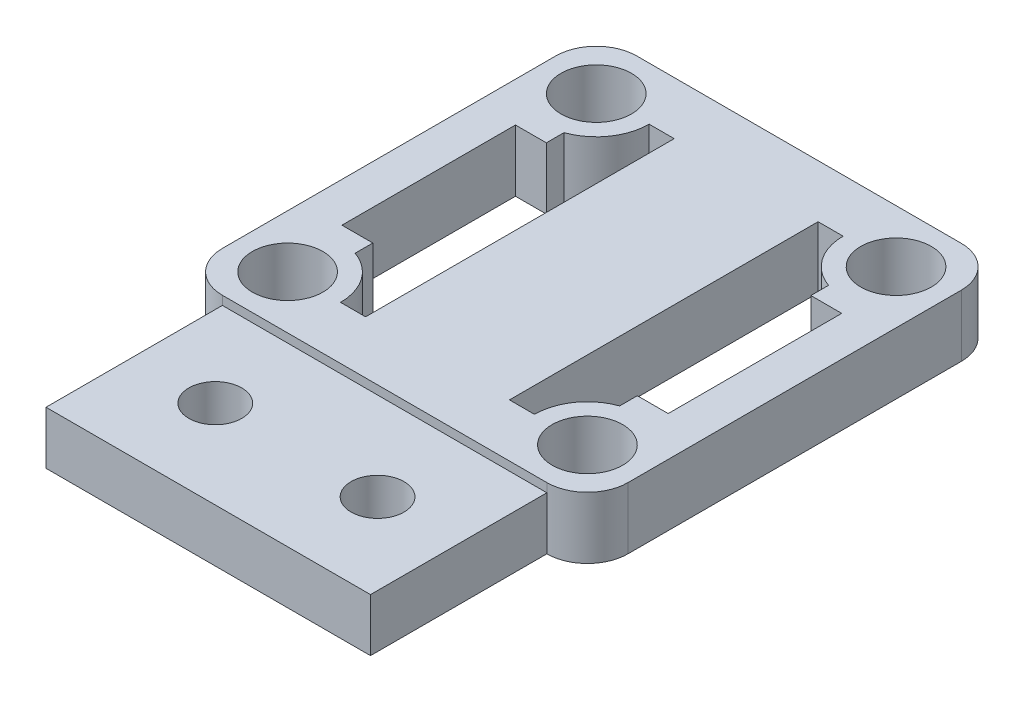
SolidWorks part; units mm, degrees
ref_plane "Front Plane" through (0, 0, 0) normal (0, 0, 1) x (1, 0, 0)
ref_plane "Top Plane" through (0, 0, 0) normal (0, 1, 0) x (1, 0, 0)
ref_plane "Right Plane" through (0, 0, 0) normal (1, 0, 0) x (0, 0, -1)
sketch "Sketch1" plane through (0, 0, 0) normal (0, 1, 0) x (1, 0, 0)
  line L1 (-12.6491, 14.6331) -> (5.7509, 14.6331)
  line L2 (-14.9491, 12.3331) -> (-14.9491, -6.5669)
  line L3 (-12.6491, -8.8669) -> (5.7509, -8.8669)
  line L4 (8.0509, 12.3331) -> (8.0509, -6.5669)
  line L5 (-14.9491, 14.6331) -> (8.0509, -8.8669) construction
  line L6 (-14.9491, -8.8669) -> (8.0509, 14.6331) construction
  arc A0 (8.0509, 12.3331) -> (5.7509, 14.6331) centre (5.7509, 12.3331) ccw
  arc A1 (-12.6491, -8.8669) -> (-14.9491, -6.5669) centre (-12.6491, -6.5669) cw
  arc A2 (5.7509, -8.8669) -> (8.0509, -6.5669) centre (5.7509, -6.5669) ccw
  arc A3 (-14.9491, 12.3331) -> (-12.6491, 14.6331) centre (-12.6491, 12.3331) cw
  point P0 (-3.4491, 2.8831)
  dimension "D3" = 2.3
  dimension "D4" = 2.3
  dimension "D1" = 23.5
  dimension "D2" = 23
extrude "Boss-Extrude1" add sketch "Sketch1" along normal blind 2
sketch "Sketch2" plane through (0, 2, 0) normal (0, 1, 0) x (1, 0, 0)
  line L8 (5.7509, 13.6331) -> (-12.6491, 13.6331)
  line L9 (-13.9491, 12.3331) -> (-13.9491, -6.5669)
  line L10 (-12.6491, -7.8669) -> (5.7509, -7.8669)
  line L11 (7.0509, -6.5669) -> (7.0509, 12.3331)
  line L12 (5.7509, 13.6331) -> (-12.6491, 13.6331)
  line L13 (-13.9491, 12.3331) -> (-13.9491, -6.5669)
  line L14 (-12.6491, -7.8669) -> (5.7509, -7.8669)
  line L15 (7.0509, -6.5669) -> (7.0509, 12.3331)
  arc A8 (7.0509, 12.3331) -> (5.7509, 13.6331) centre (5.7509, 12.3331) ccw
  arc A9 (-12.6491, 13.6331) -> (-13.9491, 12.3331) centre (-12.6491, 12.3331) ccw
  arc A10 (-13.9491, -6.5669) -> (-12.6491, -7.8669) centre (-12.6491, -6.5669) ccw
  arc A11 (5.7509, -7.8669) -> (7.0509, -6.5669) centre (5.7509, -6.5669) ccw
  arc A12 (7.0509, 12.3331) -> (5.7509, 13.6331) centre (5.7509, 12.3331) ccw
  arc A13 (-12.6491, 13.6331) -> (-13.9491, 12.3331) centre (-12.6491, 12.3331) ccw
  arc A14 (-13.9491, -6.5669) -> (-12.6491, -7.8669) centre (-12.6491, -6.5669) ccw
  arc A15 (5.7509, -7.8669) -> (7.0509, -6.5669) centre (5.7509, -6.5669) ccw
  dimension "D1" = 1
extrude "Cut-Extrude2" cut sketch "Sketch2" against normal blind 1
sketch "Sketch5" plane through (0, 1, 0) normal (0, 1, 0) x (1, 0, 0)
  line L0 (-3.4491, 13.6331) -> (-3.4491, -7.8669) construction
  line L1 (5.7509, 13.6331) -> (-12.6491, 13.6331) construction
  line L2 (-12.6491, -7.8669) -> (5.7509, -7.8669) construction
  line L3 (7.0509, 2.8831) -> (-13.9491, 2.8831) construction
  line L4 (7.0509, -6.5669) -> (7.0509, 12.3331) construction
  line L5 (-13.9491, 12.3331) -> (-13.9491, -6.5669) construction
  circle A0 centre (5.0509, 11.6331) radius 2
  circle A1 centre (5.0509, -5.8669) radius 2
  circle A2 centre (-11.9491, -5.8669) radius 2
  circle A3 centre (-11.9491, 11.6331) radius 2
  dimension "D1" = 4
extrude "Cut-Extrude3" cut sketch "Sketch5" against normal through all
sketch "Sketch6" plane through (0, 1, 0) normal (0, 1, 0) x (1, 0, 0)
  line L0 (-14.9491, 12.3331) -> (-14.9491, -6.5669) construction
  line L1 (8.0509, -6.5669) -> (8.0509, 12.3331) construction
  line L14 (4.0509, -5.8669) -> (4.0509, 11.6331)
  line L15 (4.0509, -3.0385) -> (4.0509, 8.8047)
  line L16 (2.0509, 11.6331) -> (2.0509, -5.8669)
  line L17 (-10.9491, 12.3331) -> (-10.9491, -6.5669)
  line L18 (-10.9491, 8.8047) -> (-10.9491, -3.0385)
  line L19 (-8.9491, 11.6331) -> (-8.9491, -5.8669)
  arc A5 (-11.9491, -8.8669) -> (-14.9491, -5.8669) centre (-11.9491, -5.8669) ccw
  arc A6 (-8.9491, -5.8669) -> (-10.9491, -3.0385) centre (-11.9491, -5.8669) ccw
  arc A20 (5.0509, 14.6331) -> (8.0509, 11.6331) centre (5.0509, 11.6331) ccw
  arc A21 (2.0509, 11.6331) -> (4.0509, 8.8047) centre (5.0509, 11.6331) ccw
  arc A23 (-14.9491, 11.6331) -> (-11.9491, 14.6331) centre (-11.9491, 11.6331) ccw
  arc A24 (-10.9491, 8.8047) -> (-8.9491, 11.6331) centre (-11.9491, 11.6331) ccw
  arc A26 (8.0509, -5.8669) -> (5.0509, -8.8669) centre (5.0509, -5.8669) ccw
  arc A27 (4.0509, -3.0385) -> (2.0509, -5.8669) centre (5.0509, -5.8669) ccw
  dimension "D1" = 23
  dimension "D2" = 1
  dimension "D3" = 1
  dimension "D4" = 1
  dimension "D5" = 1
  dimension "D6" = 3
  dimension "D7" = 3
extrude "Cut-Extrude4" cut sketch "Sketch6" against normal through all
sketch "Sketch7" plane through (0, 0, 8.8669) normal (0, 0, 1) x (1, 0, 0)
  line L0 (-14.9491, 2) -> (-14.9491, 0) construction
  line L1 (8.0509, 2) -> (8.0509, 0) construction
  line L2 (-12.6491, 2) -> (-12.6491, 0) construction
  line L3 (-12.6491, 1) -> (5.7509, 1)
  line L4 (5.7509, 2) -> (5.7509, 0) construction
  line L5 (5.7509, 1) -> (5.7509, 0)
  line L6 (5.7509, 0) -> (-12.6491, 0)
  line L7 (-12.6491, 0) -> (-12.6491, 1)
  line L8 (-12.6491, 2) -> (5.7509, 2) construction
  dimension "D1" = 23
extrude "Boss-Extrude2" add sketch "Sketch7" along normal blind 10
sketch "Sketch8" plane through (0, 1, 0) normal (0, 1, 0) x (1, 0, 0)
  line L0 (-12.6491, -8.8669) -> (5.7509, -8.8669) construction
  line L1 (-12.6491, -18.8669) -> (-12.6491, -8.8669) construction
  line L2 (5.7509, -18.8669) -> (5.7509, -8.8669) construction
  line L3 (-3.4491, -8.8669) -> (-3.4491, -18.8669) construction
  line L4 (5.7509, -18.8669) -> (-12.6491, -18.8669) construction
  circle A0 centre (1.1509, -13.8669) radius 1.5
  circle A1 centre (-8.0491, -13.8669) radius 1.5
  dimension "D2" = 3
  dimension "D1" = 5
  dimension "D3" = 18.4
  dimension "D4" = 4.6
  dimension "D5" = 4.6
extrude "Cut-Extrude5" cut sketch "Sketch8" against normal through all
sketch "Sketch9" plane through (0, 2, 0) normal (0, 1, 0) x (1, 0, 0)
  line L8 (5.7509, 13.8331) -> (-12.6491, 13.8331)
  line L9 (-14.1491, 12.3331) -> (-14.1491, -6.5669)
  line L10 (-12.6491, -8.0669) -> (5.7509, -8.0669)
  line L11 (7.2509, -6.5669) -> (7.2509, 12.3331)
  line L12 (5.7509, 13.8331) -> (-12.6491, 13.8331)
  line L13 (-14.1491, 12.3331) -> (-14.1491, -6.5669)
  line L14 (-12.6491, -8.0669) -> (5.7509, -8.0669)
  line L15 (7.2509, -6.5669) -> (7.2509, 12.3331)
  arc A8 (7.2509, 12.3331) -> (5.7509, 13.8331) centre (5.7509, 12.3331) ccw
  arc A9 (-12.6491, 13.8331) -> (-14.1491, 12.3331) centre (-12.6491, 12.3331) ccw
  arc A10 (-14.1491, -6.5669) -> (-12.6491, -8.0669) centre (-12.6491, -6.5669) ccw
  arc A11 (5.7509, -8.0669) -> (7.2509, -6.5669) centre (5.7509, -6.5669) ccw
  arc A12 (7.2509, 12.3331) -> (5.7509, 13.8331) centre (5.7509, 12.3331) ccw
  arc A13 (-12.6491, 13.8331) -> (-14.1491, 12.3331) centre (-12.6491, 12.3331) ccw
  arc A14 (-14.1491, -6.5669) -> (-12.6491, -8.0669) centre (-12.6491, -6.5669) ccw
  arc A15 (5.7509, -8.0669) -> (7.2509, -6.5669) centre (5.7509, -6.5669) ccw
  dimension "D1" = 0.8
extrude "Cut-Extrude6" cut sketch "Sketch9" against normal blind 1
sketch "Sketch11" plane through (0, 1, 0) normal (0, 1, 0) x (1, 0, 0)
  line L0 (-8.9491, 11.6331) -> (-7.528, 11.6331)
  line L1 (-7.528, 11.6331) -> (-7.528, -5.8669)
  line L2 (-7.528, -5.8669) -> (-8.9491, -5.8669)
  line L3 (-8.9491, -5.8669) -> (-8.9491, 11.6331)
  line L4 (-3.4491, 13.8331) -> (-3.4491, -8.0669) construction
  line L5 (5.7509, 13.8331) -> (-12.6491, 13.8331) construction
  line L6 (-12.6491, -8.0669) -> (5.7509, -8.0669) construction
  line L7 (0.6299, -5.8669) -> (2.0509, -5.8669)
  line L8 (0.6299, 11.6331) -> (0.6299, -5.8669)
  line L9 (2.0509, 11.6331) -> (0.6299, 11.6331)
  line L10 (2.0509, -5.8669) -> (2.0509, 11.6331)
  line L11 (-10.9491, 8.8047) -> (-10.9491, -3.0385) construction
  line L12 (-12.6991, 7.8031) -> (-10.9491, 7.8031)
  line L13 (-12.6991, 7.8031) -> (-12.6991, -2.0369)
  line L14 (-12.6991, -2.0369) -> (-10.9491, -2.0369)
  line L15 (-10.9491, 7.8031) -> (-10.9491, -2.0369)
  line L16 (5.8009, -2.0369) -> (4.0509, -2.0369)
  line L17 (4.0509, 7.8031) -> (4.0509, -2.0369)
  line L18 (5.8009, 7.8031) -> (4.0509, 7.8031)
  line L19 (5.8009, 7.8031) -> (5.8009, -2.0369)
  point P22 (-10.9491, 2.8831)
  point P23 (-10.9491, 2.8831)
  dimension "D1" = 9.84
  dimension "D2" = 1.75
extrude "Cut-Extrude7" cut sketch "Sketch11" against normal through all
sketch "Sketch12" plane through (0, 0, 0) normal (0, -1, 0) x (1, 0, 0)
  line L6 (8.0509, -12.3331) -> (8.0509, 6.5669)
  line L7 (5.7509, 8.8669) -> (5.7509, 18.8669)
  line L8 (5.7509, 18.8669) -> (-12.6491, 18.8669)
  line L9 (-12.6491, 18.8669) -> (-12.6491, 8.8669)
  line L10 (-14.9491, 6.5669) -> (-14.9491, -12.3331)
  line L11 (-12.6491, -14.6331) -> (5.7509, -14.6331)
  line L12 (8.0509, -12.3331) -> (8.0509, 6.5669)
  line L13 (5.7509, 8.8669) -> (5.7509, 18.8669)
  line L14 (5.7509, 18.8669) -> (-12.6491, 18.8669)
  line L15 (-12.6491, 18.8669) -> (-12.6491, 8.8669)
  line L16 (-14.9491, 6.5669) -> (-14.9491, -12.3331)
  line L17 (-12.6491, -14.6331) -> (5.7509, -14.6331)
  arc A4 (5.7509, -14.6331) -> (8.0509, -12.3331) centre (5.7509, -12.3331) ccw
  arc A5 (8.0509, 6.5669) -> (5.7509, 8.8669) centre (5.7509, 6.5669) ccw
  arc A6 (-12.6491, 8.8669) -> (-14.9491, 6.5669) centre (-12.6491, 6.5669) ccw
  arc A7 (-14.9491, -12.3331) -> (-12.6491, -14.6331) centre (-12.6491, -12.3331) ccw
  arc A8 (5.7509, -14.6331) -> (8.0509, -12.3331) centre (5.7509, -12.3331) ccw
  arc A9 (8.0509, 6.5669) -> (5.7509, 8.8669) centre (5.7509, 6.5669) ccw
  arc A10 (-12.6491, 8.8669) -> (-14.9491, 6.5669) centre (-12.6491, 6.5669) ccw
  arc A11 (-14.9491, -12.3331) -> (-12.6491, -14.6331) centre (-12.6491, -12.3331) ccw
  dimension "D1" = 0
extrude "Boss-Extrude3" add sketch "Sketch12" along normal blind 2
sketch "Sketch13" plane through (0, 0, 0) normal (0, 1, 0) x (1, 0, 0)
  line L8 (-12.6991, 7.8031) -> (-12.6991, -2.0369)
  line L9 (-12.6991, -2.0369) -> (-10.9491, -2.0369)
  line L10 (-10.9491, -2.0369) -> (-10.9491, -3.0385)
  line L11 (-8.9491, -5.8669) -> (-7.528, -5.8669)
  line L12 (-7.528, -5.8669) -> (-7.528, 11.6331)
  line L13 (-7.528, 11.6331) -> (-8.9491, 11.6331)
  line L14 (-10.9491, 8.8047) -> (-10.9491, 7.8031)
  line L15 (-10.9491, 7.8031) -> (-12.6991, 7.8031)
  line L16 (-12.6991, 7.8031) -> (-12.6991, -2.0369)
  line L17 (-12.6991, -2.0369) -> (-10.9491, -2.0369)
  line L18 (-10.9491, -2.0369) -> (-10.9491, -3.0385)
  line L19 (-8.9491, -5.8669) -> (-7.528, -5.8669)
  line L20 (-7.528, -5.8669) -> (-7.528, 11.6331)
  line L21 (-7.528, 11.6331) -> (-8.9491, 11.6331)
  line L22 (-10.9491, 8.8047) -> (-10.9491, 7.8031)
  line L23 (-10.9491, 7.8031) -> (-12.6991, 7.8031)
  arc A2 (-8.9491, -5.8669) -> (-10.9491, -3.0385) centre (-11.9491, -5.8669) ccw
  arc A3 (-10.9491, 8.8047) -> (-8.9491, 11.6331) centre (-11.9491, 11.6331) ccw
  arc A4 (-8.9491, -5.8669) -> (-10.9491, -3.0385) centre (-11.9491, -5.8669) ccw
  arc A5 (-10.9491, 8.8047) -> (-8.9491, 11.6331) centre (-11.9491, 11.6331) ccw
  dimension "D1" = 0
extrude "Cut-Extrude8" cut sketch "Sketch13" against normal through all both and the other way through all
sketch "Sketch14" plane through (0, 0, 0) normal (0, 1, 0) x (1, 0, 0)
  line L8 (0.6299, -5.8669) -> (2.0509, -5.8669)
  line L9 (4.0509, -3.0385) -> (4.0509, -2.0369)
  line L10 (4.0509, -2.0369) -> (5.8009, -2.0369)
  line L11 (5.8009, -2.0369) -> (5.8009, 7.8031)
  line L12 (5.8009, 7.8031) -> (4.0509, 7.8031)
  line L13 (4.0509, 7.8031) -> (4.0509, 8.8047)
  line L14 (2.0509, 11.6331) -> (0.6299, 11.6331)
  line L15 (0.6299, 11.6331) -> (0.6299, -5.8669)
  line L16 (0.6299, -5.8669) -> (2.0509, -5.8669)
  line L17 (4.0509, -3.0385) -> (4.0509, -2.0369)
  line L18 (4.0509, -2.0369) -> (5.8009, -2.0369)
  line L19 (5.8009, -2.0369) -> (5.8009, 7.8031)
  line L20 (5.8009, 7.8031) -> (4.0509, 7.8031)
  line L21 (4.0509, 7.8031) -> (4.0509, 8.8047)
  line L22 (2.0509, 11.6331) -> (0.6299, 11.6331)
  line L23 (0.6299, 11.6331) -> (0.6299, -5.8669)
  arc A2 (4.0509, -3.0385) -> (2.0509, -5.8669) centre (5.0509, -5.8669) ccw
  arc A3 (2.0509, 11.6331) -> (4.0509, 8.8047) centre (5.0509, 11.6331) ccw
  arc A4 (4.0509, -3.0385) -> (2.0509, -5.8669) centre (5.0509, -5.8669) ccw
  arc A5 (2.0509, 11.6331) -> (4.0509, 8.8047) centre (5.0509, 11.6331) ccw
  dimension "D1" = 0
extrude "Cut-Extrude9" cut sketch "Sketch14" against normal through all both and the other way through all
sketch "Sketch15" plane through (0, 0, 0) normal (0, 1, 0) x (1, 0, 0)
  circle A1 centre (-8.0491, -13.8669) radius 1.5
  circle A2 centre (-8.0491, -13.8669) radius 1.5
  dimension "D1" = 0
extrude "Cut-Extrude10" cut sketch "Sketch15" against normal through all both and the other way through all
sketch "Sketch16" plane through (0, 0, 0) normal (0, 1, 0) x (1, 0, 0)
  circle A1 centre (1.1509, -13.8669) radius 1.5
  circle A2 centre (1.1509, -13.8669) radius 1.5
  dimension "D1" = 0
extrude "Cut-Extrude11" cut sketch "Sketch16" against normal through all both and the other way through all
sketch "Sketch17" plane through (0, 0, 0) normal (0, 1, 0) x (1, 0, 0)
  circle A0 centre (-11.9491, -5.8669) radius 2 construction
  circle A1 centre (5.0509, -5.8669) radius 2 construction
  circle A2 centre (-11.9491, 11.6331) radius 2 construction
  circle A3 centre (5.0509, 11.6331) radius 2 construction
  circle A4 centre (-11.9491, -5.8669) radius 2
  circle A5 centre (5.0509, -5.8669) radius 2
  circle A6 centre (-11.9491, 11.6331) radius 2
  circle A7 centre (5.0509, 11.6331) radius 2
extrude "Cut-Extrude12" cut sketch "Sketch17" against normal through all both and the other way through all
sketch "Sketch18" plane through (0, 1, 0) normal (0, 1, 0) x (1, 0, 0)
  line L4 (5.7509, 13.8331) -> (-12.6491, 13.8331)
  line L5 (-14.1491, 12.3331) -> (-14.1491, -6.5669)
  line L6 (-12.6491, -8.0669) -> (5.7509, -8.0669)
  line L7 (7.2509, -6.5669) -> (7.2509, 12.3331)
  line L8 (5.7509, 13.8331) -> (-12.6491, 13.8331)
  line L9 (-14.1491, 12.3331) -> (-14.1491, -6.5669)
  line L10 (-12.6491, -8.0669) -> (5.7509, -8.0669)
  line L11 (7.2509, -6.5669) -> (7.2509, 12.3331)
  arc A4 (7.2509, 12.3331) -> (5.7509, 13.8331) centre (5.7509, 12.3331) ccw
  arc A5 (-12.6491, 13.8331) -> (-14.1491, 12.3331) centre (-12.6491, 12.3331) ccw
  arc A6 (-14.1491, -6.5669) -> (-12.6491, -8.0669) centre (-12.6491, -6.5669) ccw
  arc A7 (5.7509, -8.0669) -> (7.2509, -6.5669) centre (5.7509, -6.5669) ccw
  arc A8 (7.2509, 12.3331) -> (5.7509, 13.8331) centre (5.7509, 12.3331) ccw
  arc A9 (-12.6491, 13.8331) -> (-14.1491, 12.3331) centre (-12.6491, 12.3331) ccw
  arc A10 (-14.1491, -6.5669) -> (-12.6491, -8.0669) centre (-12.6491, -6.5669) ccw
  arc A11 (5.7509, -8.0669) -> (7.2509, -6.5669) centre (5.7509, -6.5669) ccw
  dimension "D1" = 0
extrude "Boss-Extrude4" add sketch "Sketch18" along normal up to surface (1 mm away) up to face at (-3.4491, 2, -2.8831)
sketch "Sketch19" plane through (0, 1, 0) normal (0, -1, 0) x (1, 0, 0)
  line L8 (-10.9491, 3.0385) -> (-10.9491, 2.0369)
  line L9 (-10.9491, 2.0369) -> (-12.6991, 2.0369)
  line L10 (-12.6991, 2.0369) -> (-12.6991, -7.8031)
  line L11 (-12.6991, -7.8031) -> (-10.9491, -7.8031)
  line L12 (-10.9491, -7.8031) -> (-10.9491, -8.8047)
  line L13 (-8.9491, -11.6331) -> (-7.528, -11.6331)
  line L14 (-7.528, -11.6331) -> (-7.528, 5.8669)
  line L15 (-7.528, 5.8669) -> (-8.9491, 5.8669)
  line L16 (-10.9491, 3.0385) -> (-10.9491, 2.0369)
  line L17 (-10.9491, 2.0369) -> (-12.6991, 2.0369)
  line L18 (-12.6991, 2.0369) -> (-12.6991, -7.8031)
  line L19 (-12.6991, -7.8031) -> (-10.9491, -7.8031)
  line L20 (-10.9491, -7.8031) -> (-10.9491, -8.8047)
  line L21 (-8.9491, -11.6331) -> (-7.528, -11.6331)
  line L22 (-7.528, -11.6331) -> (-7.528, 5.8669)
  line L23 (-7.528, 5.8669) -> (-8.9491, 5.8669)
  line L24 (4.0509, 2.0369) -> (4.0509, 3.0385)
  line L25 (2.0509, 5.8669) -> (0.6299, 5.8669)
  line L26 (0.6299, 5.8669) -> (0.6299, -11.6331)
  line L27 (0.6299, -11.6331) -> (2.0509, -11.6331)
  line L28 (4.0509, -8.8047) -> (4.0509, -7.8031)
  line L29 (4.0509, -7.8031) -> (5.8009, -7.8031)
  line L30 (5.8009, -7.8031) -> (5.8009, 2.0369)
  line L31 (5.8009, 2.0369) -> (4.0509, 2.0369)
  line L32 (4.0509, 2.0369) -> (4.0509, 3.0385)
  line L33 (2.0509, 5.8669) -> (0.6299, 5.8669)
  line L34 (0.6299, 5.8669) -> (0.6299, -11.6331)
  line L35 (0.6299, -11.6331) -> (2.0509, -11.6331)
  line L36 (4.0509, -8.8047) -> (4.0509, -7.8031)
  line L37 (4.0509, -7.8031) -> (5.8009, -7.8031)
  line L38 (5.8009, -7.8031) -> (5.8009, 2.0369)
  line L39 (5.8009, 2.0369) -> (4.0509, 2.0369)
  circle A0 centre (5.0509, -11.6331) radius 2 construction
  circle A1 centre (-11.9491, -11.6331) radius 2 construction
  arc A2 (-8.9491, -11.6331) -> (-10.9491, -8.8047) centre (-11.9491, -11.6331) ccw
  arc A3 (-10.9491, 3.0385) -> (-8.9491, 5.8669) centre (-11.9491, 5.8669) ccw
  arc A4 (-8.9491, -11.6331) -> (-10.9491, -8.8047) centre (-11.9491, -11.6331) ccw
  arc A5 (-10.9491, 3.0385) -> (-8.9491, 5.8669) centre (-11.9491, 5.8669) ccw
  arc A6 (2.0509, 5.8669) -> (4.0509, 3.0385) centre (5.0509, 5.8669) ccw
  arc A7 (4.0509, -8.8047) -> (2.0509, -11.6331) centre (5.0509, -11.6331) ccw
  arc A8 (2.0509, 5.8669) -> (4.0509, 3.0385) centre (5.0509, 5.8669) ccw
  arc A9 (4.0509, -8.8047) -> (2.0509, -11.6331) centre (5.0509, -11.6331) ccw
  circle A10 centre (-11.9491, 5.8669) radius 2 construction
  circle A11 centre (5.0509, 5.8669) radius 2 construction
  circle A12 centre (5.0509, -11.6331) radius 2
  circle A13 centre (-11.9491, -11.6331) radius 2
  circle A14 centre (-11.9491, 5.8669) radius 2
  circle A15 centre (5.0509, 5.8669) radius 2
  dimension "D1" = 0
  dimension "D2" = 0
extrude "Cut-Extrude13" cut sketch "Sketch19" against normal through all both and the other way through all
sketch "Sketch20" plane through (0, 2, 0) normal (0, 1, 0) x (1, 0, 0)
  line L4 (5.7509, 14.6331) -> (-12.6491, 14.6331)
  line L5 (-14.9491, 12.3331) -> (-14.9491, -6.5669)
  line L6 (-12.6491, -8.8669) -> (5.7509, -8.8669)
  line L7 (8.0509, -6.5669) -> (8.0509, 12.3331)
  line L8 (5.7509, 14.6331) -> (-12.6491, 14.6331)
  line L9 (-14.9491, 12.3331) -> (-14.9491, -6.5669)
  line L10 (-12.6491, -8.8669) -> (5.7509, -8.8669)
  line L11 (8.0509, -6.5669) -> (8.0509, 12.3331)
  arc A4 (8.0509, 12.3331) -> (5.7509, 14.6331) centre (5.7509, 12.3331) ccw
  arc A5 (-12.6491, 14.6331) -> (-14.9491, 12.3331) centre (-12.6491, 12.3331) ccw
  arc A6 (-14.9491, -6.5669) -> (-12.6491, -8.8669) centre (-12.6491, -6.5669) ccw
  arc A7 (5.7509, -8.8669) -> (8.0509, -6.5669) centre (5.7509, -6.5669) ccw
  arc A8 (8.0509, 12.3331) -> (5.7509, 14.6331) centre (5.7509, 12.3331) ccw
  arc A9 (-12.6491, 14.6331) -> (-14.9491, 12.3331) centre (-12.6491, 12.3331) ccw
  arc A10 (-14.9491, -6.5669) -> (-12.6491, -8.8669) centre (-12.6491, -6.5669) ccw
  arc A11 (5.7509, -8.8669) -> (8.0509, -6.5669) centre (5.7509, -6.5669) ccw
  dimension "D1" = 0
extrude "Cut-Extrude14" cut sketch "Sketch20" against normal blind 0.5
